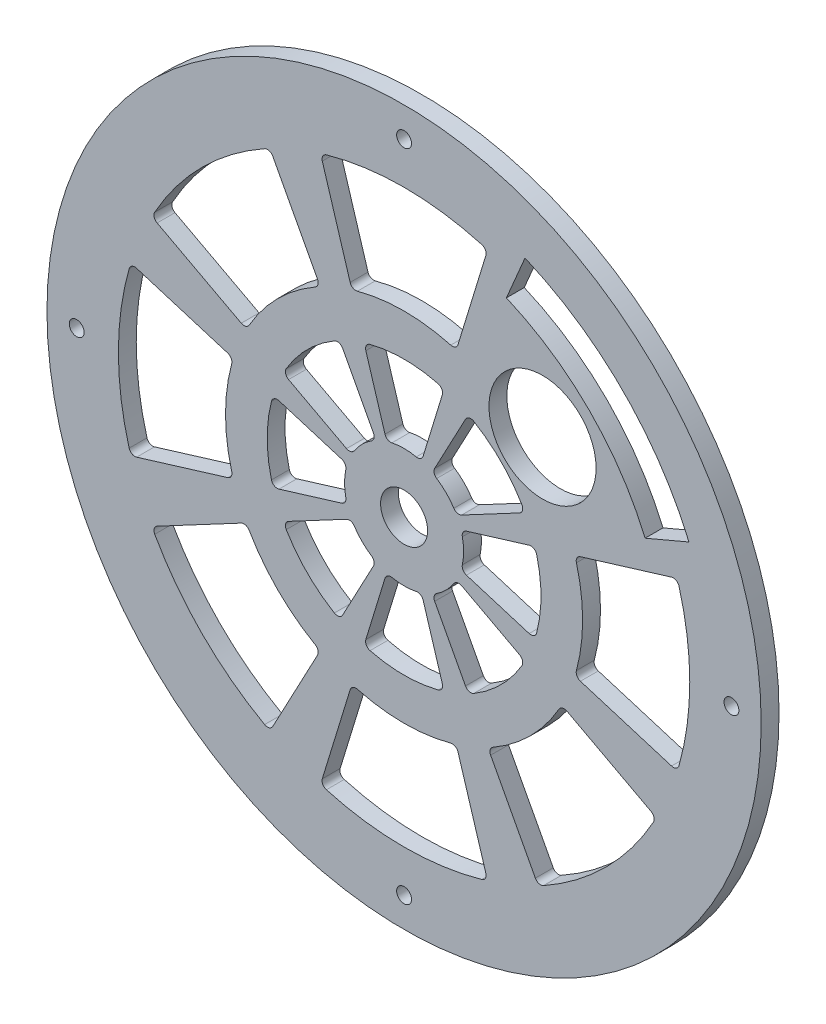
SolidWorks part; units mm, degrees
material "ABS PC"
ref_plane "前视基准面" through (0, 0, 0) normal (0, 0, 1) x (1, 0, 0)
ref_plane "上视基准面" through (0, 0, 0) normal (0, 1, 0) x (1, 0, 0)
ref_plane "右视基准面" through (0, 0, 0) normal (1, 0, 0) x (0, 0, -1)
sketch "草图1" plane through (0, 0, 0) normal (0, 0, 1) x (1, 0, 0)
  line L0 (-60, 0) -> (0, 0) construction
  line L1 (0, 0) -> (60, 0) construction
  line L2 (0, 60) -> (0, 0) construction
  line L3 (0, 0) -> (0, -60) construction
  line L4 (0, 0) -> (-42.4264, -42.4264) construction
  line L5 (0, 0) -> (42.4264, 42.4264) construction
  circle A0 centre (0, 0) radius 60
  circle A1 centre (0, 0) radius 3.95
  circle A2 centre (23.2638, 23.2638) radius 9
  circle A3 centre (0, 55) radius 1.25
  circle A4 centre (0, -55) radius 1.25
  circle A5 centre (-55, 0) radius 1.25
  circle A6 centre (55, 0) radius 1.25
  dimension "D1" = 120
  dimension "D2" = 7.9
  dimension "D6" = 55
  dimension "D7" = 18
  dimension "D3" = 45
  dimension "D4" = 45
  dimension "D5" = 32.9
extrude "凸台-拉伸1" add sketch "草图1" along normal blind 3
cosmetic thread "装饰螺纹线1" parameters "D2"=3
cosmetic thread "装饰螺纹线2" parameters "D2"=3
cosmetic thread "装饰螺纹线3" parameters "D2"=3
cosmetic thread "装饰螺纹线4" parameters "D2"=3
sketch "草图2" plane through (0, 0, 0) normal (0, 0, -1) x (-1, 0, 0)
  line L0 (0, 0) -> (-35355.3391, 35355.3391) construction
  line L4 (5.1428, -9.6722) -> (10.3177, -19.4048)
  line L5 (9.6722, -5.1428) -> (19.4048, -10.3177)
  circle A2 centre (-23.2638, 23.2638) radius 9 construction
  circle A3 centre (-23.2638, 23.2638) radius 9 construction
  arc A4 (8.3661, -5.478) -> (5.478, -8.3661) centre (0, 0) cw
  arc A5 (19.796, -11.7098) -> (11.7098, -19.796) centre (0, 0) cw
  arc A6 (8.3661, -5.478) -> (9.6722, -5.1428) centre (9.2027, -6.0258) cw
  arc A7 (5.1428, -9.6722) -> (5.478, -8.3661) centre (6.0258, -9.2027) cw
  arc A8 (19.796, -11.7098) -> (19.4048, -10.3177) centre (18.9353, -11.2006) ccw
  arc A9 (10.3177, -19.4048) -> (11.7098, -19.796) centre (11.2006, -18.9353) ccw
  point P13 (8.8295, -4.6947)
  point P16 (4.6947, -8.8295)
  point P19 (20.3078, -10.7978)
  point P22 (10.7978, -20.3078)
  dimension "D1" = 10
  dimension "D2" = 23
  dimension "D3" = 17
  dimension "D4" = 1
  dimension "D5" = 1
  dimension "D6" = 1
  dimension "D7" = 1
extrude "切除-拉伸2" cut sketch "草图2" against normal through all
pattern_circular "阵列(圆周)1" count 8 over 360 about axis through (0, 0, 0) along (0, 0, 1) of "切除-拉伸2"
sketch "草图3" plane through (0, 0, 0) normal (0, 0, -1) x (-1, 0, 0)
  line L0 (0, 0) -> (-35204.5011, 35204.5011) construction
  line L1 (14.546, -27.3571) -> (22.0602, -41.4891)
  line L2 (27.3571, -14.546) -> (41.4891, -22.0602)
  circle A0 centre (-23.2638, 23.2638) radius 9 construction
  circle A1 centre (-23.2638, 23.2638) radius 9 construction
  arc A2 (26.0203, -14.9313) -> (14.9313, -26.0203) centre (0, 0) cw
  arc A3 (41.8924, -23.4313) -> (23.4313, -41.8924) centre (0, 0) cw
  arc A4 (41.8924, -23.4313) -> (41.4891, -22.0602) centre (41.0197, -22.9431) ccw
  arc A5 (22.0602, -41.4891) -> (23.4313, -41.8924) centre (22.9431, -41.0197) ccw
  arc A6 (14.546, -27.3571) -> (14.9313, -26.0203) centre (15.429, -26.8877) cw
  arc A7 (26.0203, -14.9313) -> (27.3571, -14.546) centre (26.8877, -15.429) cw
  point P14 (42.3815, -22.5346)
  point P17 (22.5346, -42.3815)
  point P20 (14.0841, -26.4884)
  point P23 (26.4884, -14.0841)
  dimension "D1" = 30
  dimension "D2" = 48
  dimension "D4" = 1
  dimension "D3" = 17
extrude "切除-拉伸3" cut sketch "草图3" against normal through all
pattern_circular "阵列(圆周)2" count 4 every 45 about axis through (0, 0, 0) along (0, 0, 1) of "切除-拉伸3"
pattern_circular "阵列(圆周)3" count 4 every 45 about axis through (0, 0, 0) along (0, 0, 1) of "切除-拉伸3"
sketch "草图4" plane through (0, 0, 0) normal (0, 0, -1) x (-1, 0, 0)
  line L0 (-19.8776, 19.8776) -> (35335.4615, -35335.4615) construction
  line L1 (-47.8663, 20.318) -> (-40.5022, 17.1922)
  line L2 (-20.318, 47.8663) -> (-17.1922, 40.5022)
  circle A0 centre (-23.2638, 23.2638) radius 9 construction
  circle A3 centre (-23.2638, 23.2638) radius 9 construction
  arc A4 (-17.1922, 40.5022) -> (-40.5022, 17.1922) centre (0, 0) ccw
  arc A5 (-20.318, 47.8663) -> (-47.8663, 20.318) centre (0, 0) ccw
  dimension "D3" = 44
  dimension "D4" = 52
  dimension "D2" = 22
extrude "切除-拉伸6" cut sketch "草图4" against normal through all
